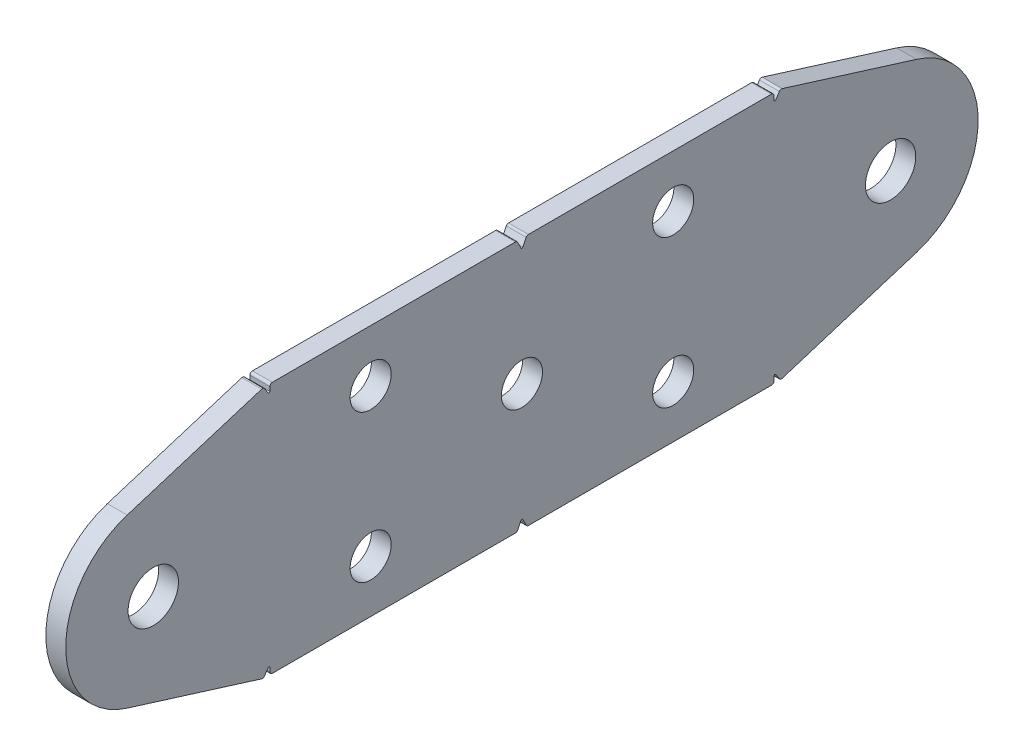
SolidWorks part; units mm, degrees
ref_plane "Front Plane" through (0, 0, 0) normal (0, 0, 1) x (1, 0, 0)
ref_plane "Top Plane" through (0, 0, 0) normal (0, 1, 0) x (1, 0, 0)
ref_plane "Right Plane" through (0, 0, 0) normal (1, 0, 0) x (0, 0, -1)
sketch "Sketch1" plane through (0, 0, 0) normal (1, 0, 0) x (0, 0, -1)
  line L0 (0, 0) -> (0, -14.149) construction
  line L1 (25.4, 50.1181) -> (25.4, 12.3902) construction
  line L2 (-25.4, 50.1181) -> (-25.4, 12.3902) construction
  line L3 (-63.7076, 0) -> (-32.135, 0) construction
  line L4 (-26.035, 12.7) -> (26.035, 12.7)
  line L5 (-26.035, 0) -> (-26.035, -12.7) construction
  line L6 (-26.035, -12.7) -> (26.035, -12.7)
  line L7 (26.035, 0) -> (26.035, -12.7) construction
  line L8 (-26.035, 12.7) -> (26.035, -12.7) construction
  line L9 (-26.035, -12.7) -> (26.035, 12.7) construction
  line L10 (-26.035, 12.7) -> (-39.7701, 8.4237)
  line L11 (-26.035, -12.7) -> (-39.7701, -8.4237)
  line L12 (26.035, -12.7) -> (39.7701, -8.4237)
  line L13 (26.035, 12.7) -> (39.7701, 8.4237)
  line L14 (-26.035, 12.7) -> (-26.035, 0) construction
  line L15 (-25.4, 12.3902) -> (-25.4, 0) construction
  line L16 (-25.4, -12.3902) -> (-25.4, -1023.3544) construction
  line L17 (-25.4, 0) -> (-25.4, -12.3902) construction
  line L18 (-26.035, 0) -> (-25.4, 0) construction
  line L19 (-25.4, 0) -> (25.4, 0) construction
  line L20 (25.4, 12.3902) -> (25.4, 0) construction
  line L21 (25.4, -12.3902) -> (25.4, -1023.3544) construction
  line L22 (26.035, 12.7) -> (26.035, 0) construction
  line L23 (25.4, 0) -> (26.035, 0) construction
  line L24 (26.035, 0) -> (28.325, 0) construction
  line L25 (25.4, 0) -> (25.4, -12.3902) construction
  line L26 (28.325, 0) -> (32.135, 0) construction
  line L27 (32.135, 0) -> (78.2006, 0) construction
  line L28 (-32.135, 0) -> (-28.325, 0) construction
  line L29 (-28.325, 0) -> (-26.035, 0) construction
  arc A0 (-33.319, 10.4322) -> (-33.319, -10.4322) centre (-37.1475, 0) ccw construction
  circle A1 centre (-37.1475, 0) radius 5.0125 construction
  arc A2 (-39.7701, 8.4237) -> (-39.7701, -8.4237) centre (-37.1475, 0) ccw
  circle A3 centre (37.1475, 0) radius 5.0125 construction
  arc A4 (39.7701, 8.4237) -> (39.7701, -8.4237) centre (37.1475, 0) cw
  arc A5 (-26.035, 0) -> (-33.319, 10.4322) centre (-37.1475, 0) ccw construction
  arc A6 (-33.319, -10.4322) -> (-26.035, 0) centre (-37.1475, 0) ccw construction
  arc A7 (28.325, 0) -> (39.7701, 8.4237) centre (37.1475, 0) cw construction
  arc A8 (39.7701, -8.4237) -> (28.325, 0) centre (37.1475, 0) cw construction
  arc A9 (-28.325, 0) -> (-39.7701, 8.4237) centre (-37.1475, 0) ccw construction
  circle A10 centre (-37.1475, 0) radius 8.8225 construction
  arc A11 (-39.7701, -8.4237) -> (-28.325, 0) centre (-37.1475, 0) ccw construction
  circle A12 centre (0, 0) radius 2.07
  circle A13 centre (-15.24, 7.4341) radius 2.07
  circle A14 centre (-15.24, -7.4341) radius 2.07
  circle A15 centre (15.24, -7.4341) radius 2.07
  circle A16 centre (15.24, 7.4341) radius 2.07
  circle A17 centre (-37.1475, 0) radius 2.5375
  circle A18 centre (37.1475, 0) radius 2.5375
  point P8 (0, 0)
  dimension "D4" = 22.225
  dimension "D5" = 10.025
  dimension "D7" = 4.14
  dimension "D9" = 5.075
  dimension "D1" = 25.4
  dimension "D2" = 52.07
  dimension "D3" = 25.4
  dimension "D8" = 15.24
  dimension "D6" = 3.81
extrude "Boss-Extrude1" add sketch "Sketch1" along normal mid plane 2
sketch "Sketch2" plane through (1, 0, 0) normal (1, 0, 0) x (0, 0, -1)
  line L0 (0, 0) -> (0, 12.7) construction
  line L1 (26.035, 12.7) -> (-26.035, 12.7) construction
  line L2 (-25.4, 12.7) -> (-25.4, 12.044)
  line L3 (-25.5844, 11.9904) -> (-26.035, 12.7)
  line L4 (-26.035, 12.7) -> (-39.7701, 8.4237) construction
  line L5 (-25.4, 12.7) -> (-26.035, 12.7)
  line L6 (25.4, 12.7) -> (25.4, 12.044)
  line L7 (25.5844, 11.9904) -> (26.035, 12.7)
  line L8 (25.4, 12.7) -> (26.035, 12.7)
  line L9 (0, 0) -> (-37.1475, 0) construction
  line L10 (25.4, -12.7) -> (26.035, -12.7)
  line L11 (25.5844, -11.9904) -> (26.035, -12.7)
  line L12 (25.4, -12.7) -> (25.4, -12.044)
  line L13 (-25.4, -12.7) -> (-25.4, -12.044)
  line L14 (-25.5844, -11.9904) -> (-26.035, -12.7)
  line L15 (-25.4, -12.7) -> (-26.035, -12.7)
  line L16 (-0.5, 12.7) -> (0.5, 12.7)
  line L17 (-0.5, 12.7) -> (-0.0894, 11.8789)
  line L18 (0.5, 12.7) -> (0.0894, 11.8789)
  line L19 (-0.5, -12.7) -> (0.5, -12.7)
  line L20 (-0.5, -12.7) -> (-0.0894, -11.8789)
  line L21 (0.5, -12.7) -> (0.0894, -11.8789)
  arc A0 (-25.4, 12.044) -> (-25.5844, 11.9904) centre (-25.5, 12.044) cw
  arc A1 (25.4, 12.044) -> (25.5844, 11.9904) centre (25.5, 12.044) ccw
  arc A2 (25.4, -12.044) -> (25.5844, -11.9904) centre (25.5, -12.044) cw
  arc A3 (-25.4, -12.044) -> (-25.5844, -11.9904) centre (-25.5, -12.044) ccw
  arc A4 (-0.0894, -11.8789) -> (0.0894, -11.8789) centre (0, -11.9236) cw
  arc A5 (-0.0894, 11.8789) -> (0.0894, 11.8789) centre (0, 11.9236) ccw
  point P12 (-25.4, 11.7)
  point P33 (0, 12.7)
  point P39 (0, -11.7)
  point P42 (0, 11.7)
  dimension "D3" = 0.1
  dimension "D6" = 0.1
  dimension "D1" = 1
  dimension "D2" = 25.4
  dimension "D4" = 1
  dimension "D5" = 1
extrude "Cut-Extrude1" cut sketch "Sketch2" against normal through all both and the other way through all
fillet "Fillet1" radius 0.25 12 edges at (0, -12.7, 26.035) (0, -12.7, 25.4) (0, -12.7, -25.4) (0, -12.7, -26.035) (0, 12.7, -25.4) (0, 12.7, -26.035) (0, 12.7, 26.035) (0, 12.7, 25.4) (0, -12.7, 0.5) (0, -12.7, -0.5) (0, 12.7, -0.5) (0, 12.7, 0.5)
